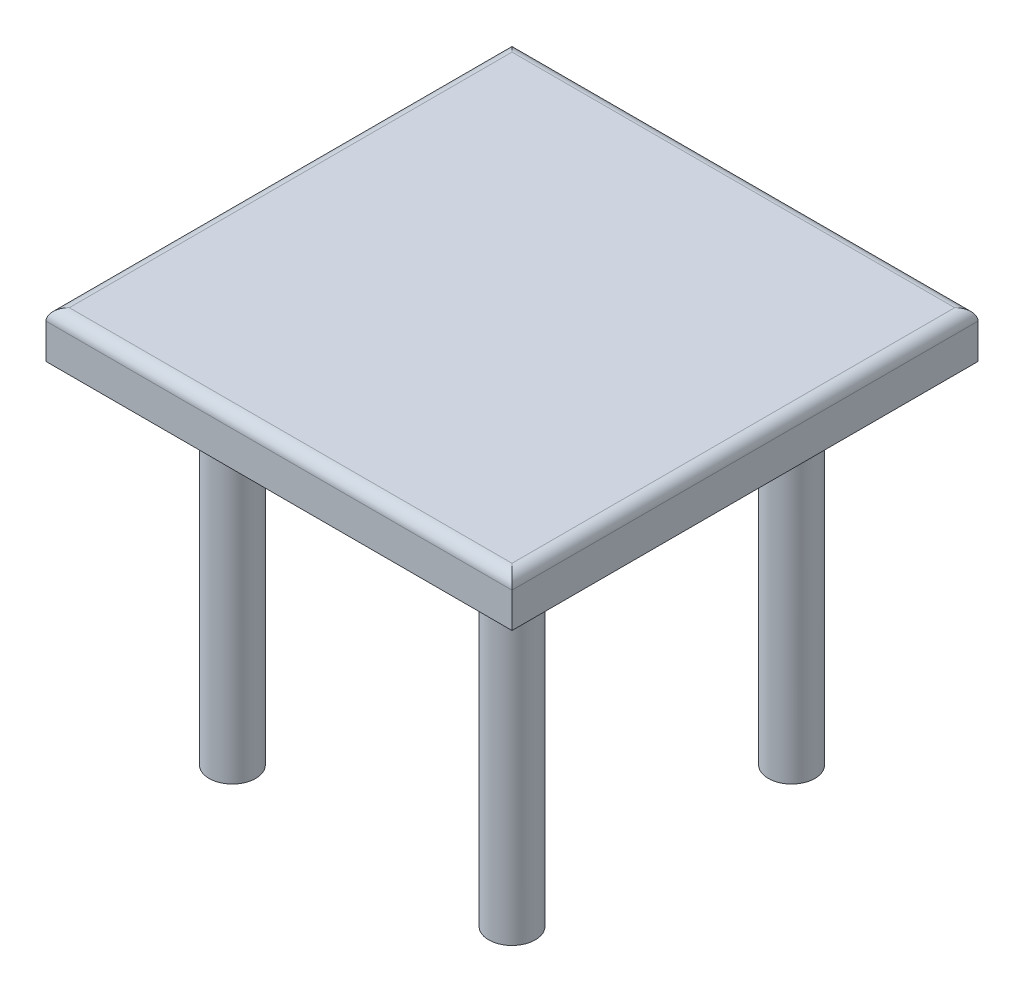
SolidWorks part; units mm, degrees
ref_plane "前视基准面" through (0, 0, 0) normal (0, 0, 1) x (1, 0, 0)
ref_plane "上视基准面" through (0, 0, 0) normal (0, 1, 0) x (1, 0, 0)
ref_plane "右视基准面" through (0, 0, 0) normal (1, 0, 0) x (0, 0, -1)
sketch "草图1" plane through (0, 0, 0) normal (0, 1, 0) x (1, 0, 0)
  line L0 (-100, 100) -> (100, 100)
  line L1 (100, 100) -> (100, -100)
  line L2 (100, -100) -> (-100, -100)
  line L3 (-100, -100) -> (-100, 100)
extrude "凸台-拉伸1" add sketch "草图1" against normal blind 20
ref_plane "基准面1" through (0, -20, 0) normal (0, 1, 0) x (1, 0, 0)
fillet "圆角1" radius 5 4 edges at (-100, 0, 0) (100, 0, 0) (0, 0, -100) (0, 0, 100)
sketch "草图4" plane through (0, -20, 0) normal (0, 1, 0) x (1, 0, 0)
  circle A0 centre (-60, 60) radius 10
  circle A1 centre (60, 60) radius 10
  circle A2 centre (-60, -60) radius 10
  circle A3 centre (60, -60) radius 10
extrude "凸台-拉伸4" add sketch "草图4" against normal blind 150
